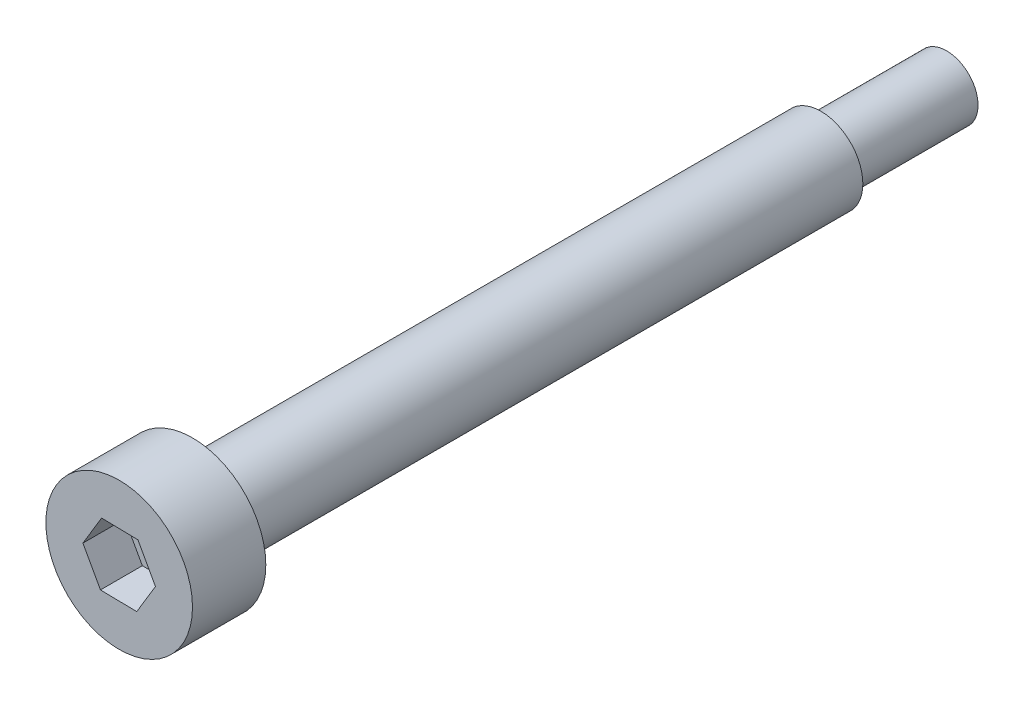
SolidWorks part; units mm, degrees
material "AISI 304"
ref_plane "前视基准面" through (0, 0, 0) normal (0, 0, 1) x (1, 0, 0)
ref_plane "上视基准面" through (0, 0, 0) normal (0, 1, 0) x (1, 0, 0)
ref_plane "右视基准面" through (0, 0, 0) normal (1, 0, 0) x (0, 0, -1)
sketch "草图1" plane through (0, 0, 0) normal (0, 0, 1) x (1, 0, 0)
  circle A0 centre (0, 0) radius 3.5
  dimension "D1" = 7
extrude "凸台-拉伸1" add sketch "草图1" along normal blind 3.5
sketch "草图2" plane through (0, 0, 3.5) normal (0, 0, 1) x (1, 0, 0)
  line L1 (0.8936, 1.4837) -> (-0.8381, 1.5158)
  line L2 (-0.8381, 1.5158) -> (-1.7318, 0.0321)
  line L3 (-1.7318, 0.0321) -> (-0.8936, -1.4837)
  line L4 (-0.8936, -1.4837) -> (0.8381, -1.5158)
  line L5 (0.8381, -1.5158) -> (1.7318, -0.0321)
  line L6 (1.7318, -0.0321) -> (0.8936, 1.4837)
  circle A0 centre (0, 0) radius 1.5 construction
  dimension "D1" = 3
extrude "切除-拉伸1" cut sketch "草图2" against normal blind 2
sketch "草图3" plane through (0, 0, 0) normal (0, 0, -1) x (-1, 0, 0)
  circle A0 centre (0, 0) radius 2
  dimension "D1" = 4
extrude "凸台-拉伸2" add sketch "草图3" along normal blind 30
sketch "草图4" plane through (0, 0, -30) normal (0, 0, -1) x (-1, 0, 0)
  circle A0 centre (0, 0) radius 1.5
  dimension "D1" = 3
extrude "凸台-拉伸3" add sketch "草图4" along normal blind 6
cosmetic thread "装饰螺纹线1" parameters "D2"=2
